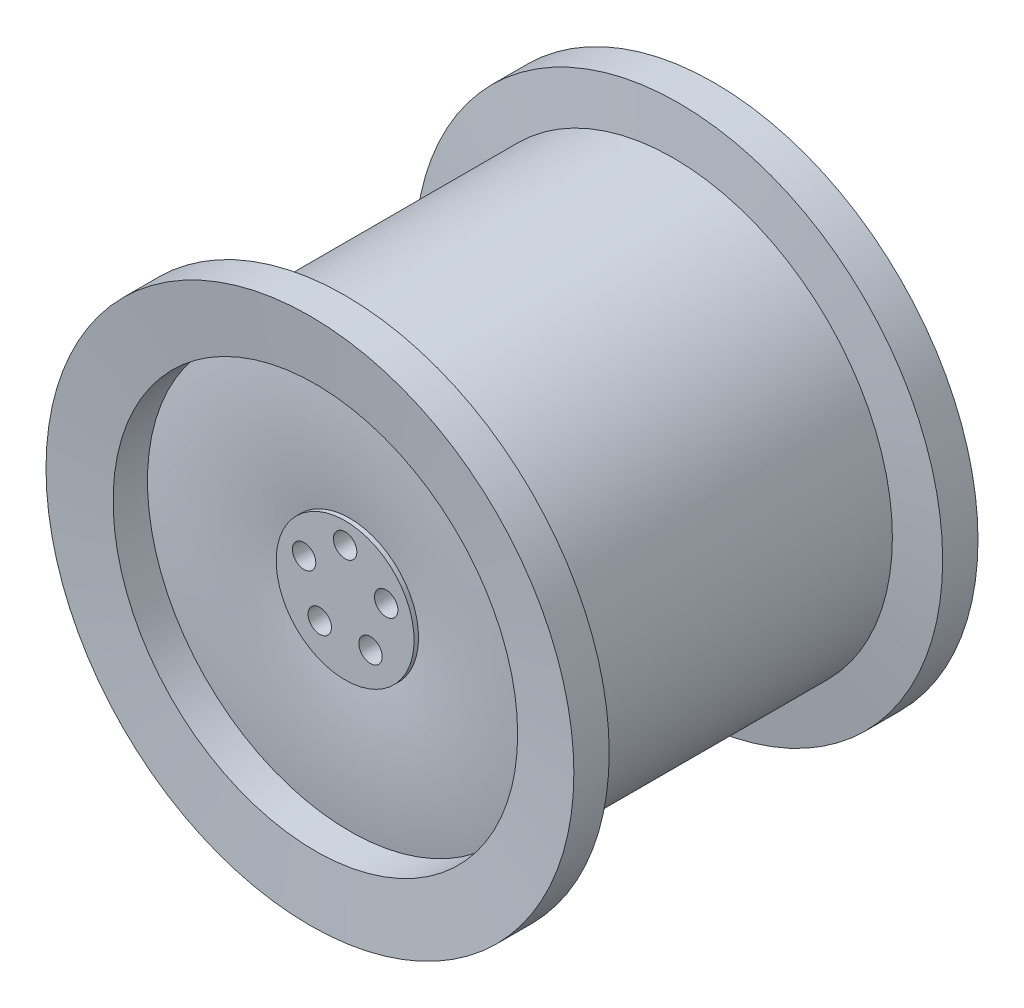
SolidWorks part; units mm, degrees
ref_plane "Front Plane" through (0, 0, 0) normal (0, 0, 1) x (1, 0, 0)
ref_plane "Top Plane" through (0, 0, 0) normal (0, 1, 0) x (1, 0, 0)
ref_plane "Right Plane" through (0, 0, 0) normal (1, 0, 0) x (0, 0, -1)
sketch "Sketch1" plane through (0, 0, 0) normal (0, 0, 1) x (1, 0, 0)
  line L1 (0, -43.6846) -> (0, 43.6846) construction
  circle A0 centre (0, 4.4916) radius 39.7133
sketch "Sketch3" plane through (0, 0, 0) normal (1, 0, 0) x (0, 0, -1)
  line L0 (29.1003, 44.0262) -> (-29.1003, 44.0262)
  line L7 (29.1003, 44.0262) -> (30.0855, 52.1145)
  line L8 (30.0855, 52.1145) -> (36.4601, 52.1145)
  line L9 (36.4601, 52.1145) -> (35.4782, 40.989)
  line L10 (35.4782, 40.989) -> (-35.4782, 40.989)
  line L11 (-36.4601, 52.1145) -> (-35.4782, 40.989)
  line L12 (-30.0855, 52.1145) -> (-36.4601, 52.1145)
  line L14 (-29.1003, 44.0262) -> (-30.0855, 52.1145)
  point P0 (0, 40.989)
  point P14 (0, 40.989)
sketch "Sketch4" plane through (0, 0, 0) normal (1, 0, 0) x (0, 0, -1)
  line L2 (-34.869, 4.4916) -> (42.0181, 4.4916)
revolve "Revolve2" add sketch "Sketch3" angle 360 about L2
ref_plane "Plane1" through (0, 0, 22.1472) normal (0, 0, 1) x (1, 0, 0)
sketch "Sketch8" plane through (0, 0, 22.1472) normal (0, 0, 1) x (1, 0, 0)
  circle A1 centre (0, 4.4916) radius 12.4458
extrude "Boss-Extrude2" add sketch "Sketch8" along normal blind 7.9614 separate body contours A1
ref_plane "Plane3" through (0, 0, 40.64) normal (0, 0, 1) x (1, 0, 0)
sketch "Sketch10" plane through (0, 0, 40.64) normal (0, 0, 1) x (1, 0, 0)
  circle A0 centre (0, 13.0958) radius 2.1104
  circle A1 centre (7.4072, 7.7141) radius 2.1104
  circle A2 centre (4.5779, -0.9935) radius 2.1104
  circle A3 centre (-4.5779, -0.9935) radius 2.1104
  circle A4 centre (-7.4072, 7.7141) radius 2.1104
  point P2 (-8.3265, 4.1518)
  point P3 (0, 13.8526)
  point P4 (0, 7.0125)
  point P13 (0, 5.3074)
  point P14 (0, 0)
  point P15 (0, 2.2009)
  point P16 (0, 9.8075)
  point P17 (0, 3.8933)
  point P18 (0, 14.8724)
  point P19 (0, 5.8504)
  point P20 (0, 13.8502)
  point P21 (-5.1165, -1.1897)
  point P22 (0, 0)
  point P23 (0, 5.2363)
  point P24 (0, 7.2591)
  point P25 (0, 5.3074)
  point P26 (0, 13.0958)
  dimension "D1" = 5
extrude "Cut-Extrude1" cut sketch "Sketch10" against normal blind 137.414
sketch "Sketch12" plane through (0, 0, 0) normal (1, 0, 0) x (0, 0, -1)
  line L2 (-29.1003, 44.0262) -> (-29.1003, -35.043) construction
  line L3 (-29.1003, 42.1931) -> (-26.5414, 42.1931)
  line L4 (-29.1003, 15.5839) -> (-26.5414, 15.5839)
  spline S0 degree 2 poles (-29.1003, 42.1931) (-31.1921, 28.8805) (-29.1003, 15.5839) knots 0 0 0 1 1 1
  spline S1 degree 2 poles (-26.5414, 42.1931) (-29.1064, 28.8765) (-26.5414, 15.5839) knots 0 0 0 1 1 1
revolve "Revolve4" add sketch "Sketch12" angle 360 about L2
sketch "Sketch13" plane through (0, 0, 40.64) normal (0, 0, 1) x (1, 0, 0)
  line L1 (2.0841, 40.9294) -> (2.0841, 18.3244)
  line L2 (-1.8119, 40.941) -> (-1.8119, 18.3627)
  line L3 (35.1519, 14.3102) -> (13.6961, 7.3388)
  line L4 (33.9049, 18.0015) -> (12.3788, 11.0073)
  line L5 (20.022, -26.0236) -> (6.7525, -7.7596)
  line L6 (23.1607, -23.7154) -> (9.8697, -5.4219)
  line L7 (-23.3701, -23.5405) -> (-10.0633, -5.2253)
  line L8 (-20.2407, -25.8615) -> (-6.9911, -7.625)
  line L9 (-33.8022, 18.2544) -> (-12.2475, 11.2508)
  line L10 (-35.0778, 14.5723) -> (-13.6378, 7.606)
  arc A0 (9.1922, 15.0364) -> (6.6519, 16.7978) centre (0, 4.4916) ccw
  circle A1 centre (0, 4.4916) radius 36.4974 construction
  circle A2 centre (0, 4.4916) radius 36.4974 construction
  arc A3 (13.6961, 7.3388) -> (12.3788, 11.0073) centre (0, 4.4916) ccw
  circle A5 centre (0, 4.4916) radius 36.4974
  arc A6 (12.6731, -1.4314) -> (13.8842, 2.783) centre (0, 4.4916) ccw
  arc A7 (6.7525, -7.7596) -> (9.8697, -5.4219) centre (0, 4.4916) ccw
  arc A8 (-2.5831, -9.2567) -> (2.5831, -9.2567) centre (0, 4.4916) ccw
  arc A9 (-10.0633, -5.2253) -> (-6.9911, -7.625) centre (0, 4.4916) ccw
  arc A10 (-13.8842, 2.783) -> (-12.6731, -1.4314) centre (0, 4.4916) ccw
  arc A11 (-12.2475, 11.2508) -> (-13.6378, 7.606) centre (0, 4.4916) ccw
  arc A12 (-6.6519, 16.7978) -> (-9.1922, 15.0364) centre (0, 4.4916) ccw
  arc A13 (2.0841, 18.3244) -> (-1.8119, 18.3627) centre (0, 4.4916) ccw
  spline S0 degree 2 poles (3.5165, 40.8192) (3.9112, 28.6637) (6.6519, 16.7978) knots 0 0 0 1 1 1
  spline S1 degree 2 poles (-3.5167, 40.8162) (-3.9115, 28.6622) (-6.6519, 16.7978) knots 0 0 0 1 1 1
  spline S2 degree 3 poles (35.4971, 12.9777) (27.524, 10.0322) (20.6364, 6.7831) (13.8842, 2.783) knots 0 0 0 0 0.967271 0.967271 0.967271 0.967271
  spline S3 degree 3 poles (33.2205, 19.6064) (25.008, 17.1632) (17.2445, 15.7468) (9.1922, 15.0364) knots 0 0 0 0 0.995735 0.995735 0.995735 0.995735
  spline S4 degree 3 poles (18.7445, -26.6509) (13.2465, -19.5767) (8.2862, -14.3284) (2.5831, -9.2567) knots 0 0 0 0 0.941083 0.941083 0.941083 0.941083
  spline S5 degree 3 poles (24.4812, -22.5739) (19.2335, -15.0054) (15.7668, -8.56) (12.6731, -1.4314) knots 0 0 0 0 0.957921 0.957921 0.957921 0.957921
  spline S6 degree 3 poles (-24.5144, -22.5413) (-19.2198, -15.0189) (-15.7668, -8.56) (-12.6731, -1.4314) knots 0 0 0 0 0.957921 0.957921 0.957921 0.957921
  spline S7 degree 3 poles (-18.8052, -26.7528) (-13.2223, -19.5361) (-8.2862, -14.3284) (-2.5831, -9.2567) knots 0 0 0 0 0.941083 0.941083 0.941083 0.941083
  spline S8 degree 3 poles (-33.2287, 19.5743) (-25.0044, 17.1773) (-17.2445, 15.7468) (-9.1922, 15.0364) knots 0 0 0 0 0.995735 0.995735 0.995735 0.995735
  spline S9 degree 3 poles (-35.5141, 12.8965) (-27.5169, 10.0663) (-20.6364, 6.7831) (-13.8842, 2.783) knots 0 0 0 0 0.967271 0.967271 0.967271 0.967271
  point P1 (33.2205, 19.6064)
  point P2 (33.9264, 17.9474)
  point P4 (35.0766, 14.5756)
  point P54 (35.4971, 12.9777)
  point P57 (18.7445, -26.6509)
  point P62 (20.1913, -25.9006)
  point P63 (0, 5.08)
  point P64 (23.118, -23.7505)
  point P65 (24.3392, -22.4086)
  point P66 (-24.3705, -22.4086)
  point P67 (0, 0)
  point P68 (0, 0)
  point P69 (-23.2584, -23.4785)
  point P70 (-20.2092, -25.7343)
  point P71 (-18.7369, -26.6509)
  point P72 (-34.9657, 14.5722)
  point P73 (0, 0)
  point P74 (0, 0)
  point P75 (-35.4246, 12.8825)
  point P76 (0, 0)
  point P77 (0, 0)
  point P78 (-33.2146, 19.5071)
  point P79 (0, 0)
  point P80 (0, 0)
  point P81 (-33.8662, 18.2581)
  point P82 (0, 0)
  point P83 (-33.3616, 19.6064)
  point P84 (-35.0851, 14.5975)
  point P85 (-35.536, 12.9031)
  point P86 (-35.5141, 12.8965)
  point P87 (-35.071, 14.594)
  point P88 (-35.0708, 14.5939)
  point P89 (-33.8071, 18.2395)
  point P90 (-33.2287, 19.5743)
  point P91 (-20.2408, -25.8614)
  point P92 (-18.8052, -26.7528)
  point P93 (-23.3753, -23.5364)
  point P94 (-24.5061, -22.542)
  point P95 (-1.8119, 40.941)
  point P96 (-3.5167, 40.8162)
  point P97 (2.0912, 40.929)
  point P98 (2.0909, 40.929)
  point P99 (2.0895, 40.9291)
  point P100 (2.0844, 40.9294)
  point P101 (2.0844, 40.9294)
  point P102 (2.084, 40.9294)
  point P103 (2.0841, 40.9294)
  point P104 (24.4667, -22.5562)
  point P105 (24.4813, -22.5737)
  point P106 (24.4815, -22.5739)
  point P107 (24.4801, -22.5727)
  point P108 (0, 0)
  point P109 (24.4812, -22.5739)
  point P110 (-24.4741, -22.4945)
  point P111 (-23.3701, -23.5405)
  point P112 (-24.5163, -22.5438)
  point P113 (-24.5153, -22.5422)
  point P114 (-24.5144, -22.5413)
  point P115 (-24.5144, -22.5413)
  dimension "D1" = 5
